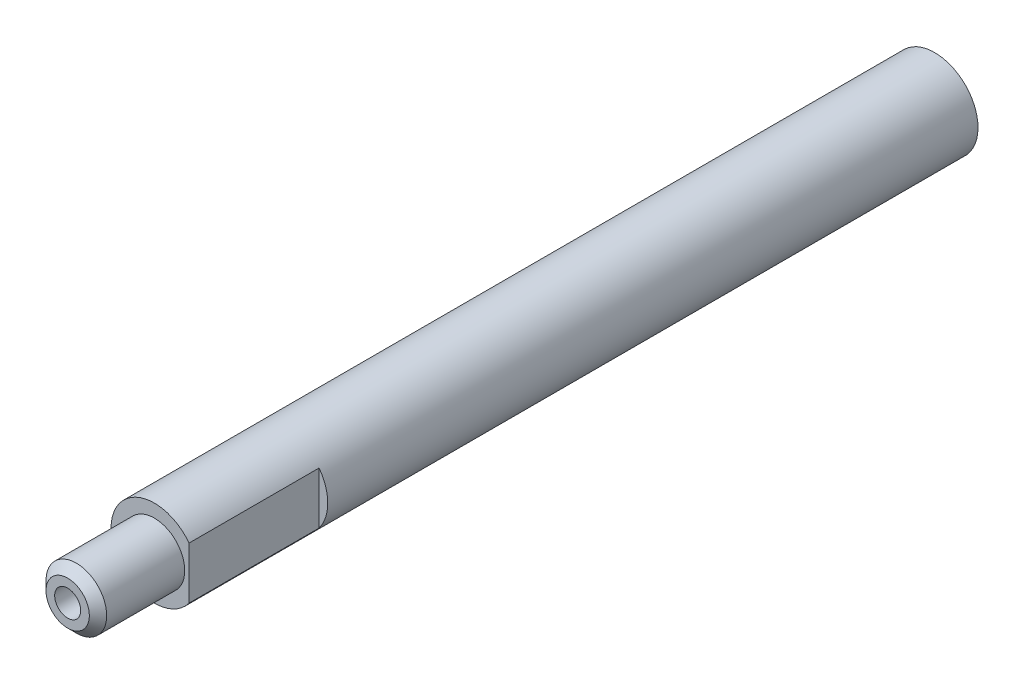
SolidWorks part; units mm, degrees
ref_plane "Front Plane" through (0, 0, 0) normal (0, 0, 1) x (1, 0, 0)
ref_plane "Top Plane" through (0, 0, 0) normal (0, 1, 0) x (1, 0, 0)
ref_plane "Right Plane" through (0, 0, 0) normal (1, 0, 0) x (0, 0, -1)
sketch "Sketch1" plane through (0, 0, 0) normal (0, 0, 1) x (1, 0, 0)
  circle A0 centre (0, 0) radius 5
  dimension "D1" = 10
extrude "Base Extrude" add sketch "Sketch1" along normal blind 100
sketch "Sketch7" plane through (0, 0, 100) normal (0, 0, 1) x (1, 0, 0)
  circle A0 centre (0, 0) radius 3.5
  dimension "D1" = 7
extrude "Front Cut" cut sketch "Sketch7" against normal blind 10 flip side to cut
hole_wizard "Front Hole" positions "Sketch2" profile "Sketch3" hole size "Ø3.0" standard "ANSI Metric"
sketch "Sketch2" plane through (0, 0, 100) normal (0, 0, 1) x (1, 0, 0)
  point P0 (0, 0)
sketch "Sketch3" plane through (0, 0, 100) normal (1, 0, 0) x (0, -1, 0)
  line L0 (0, 0) -> (0, 10.9013)
  line L1 (0, 10.9013) -> (1.5, 10)
  line L2 (1.5, 10) -> (1.5, 0)
  line L5 (1.5, 0) -> (0, 0)
  line L10 (0, 10.9013) -> (-1.5, 10) construction
  line L11 (0, -6.35) -> (0, 107.95) construction
  dimension "Hole Dia." = 3
  dimension "Hole Depth" = 10
  dimension "Drill Angle" = 118
chamfer "Chamfer1" distance 1 angle 45 1 edges at (3.5, 0, 100)
sketch "Keyway" plane through (0, 0, 90) normal (0, 0, 1) x (1, 0, 0)
  line L0 (4, 3) -> (4, -3)
  circle A1 centre (0, 0) radius 2.5
  circle A3 centre (0, 0) radius 5 construction
  circle A4 centre (0, 0) radius 2.5
  arc A5 (4, -3) -> (4, 3) centre (0, 0) ccw
  dimension "D2" = 6
  dimension "D1" = 0
extrude "Keyway Cut" cut sketch "Keyway" against normal blind 15 contours A5 L0
hole_wizard "Ø4.0 (4) Black Hole" positions "Sketch5" profile "Sketch6" hole size "Ø4.0" standard "ANSI Metric"
sketch "Sketch5" plane through (0, 0, 0) normal (0, 0, -1) x (-1, 0, 0)
  point P0 (0, 0)
sketch "Sketch6" plane through (0, 0, 0) normal (1, 0, 0) x (0, 1, 0)
  line L0 (0, 0) -> (0, 21.2017)
  line L1 (0, 21.2017) -> (2, 20)
  line L2 (2, 20) -> (2, 0)
  line L5 (2, 0) -> (0, 0)
  line L10 (0, 21.2017) -> (-2, 20) construction
  line L11 (0, -6.35) -> (0, 107.95) construction
  dimension "Hole Dia." = 4
  dimension "Hole Depth" = 20
  dimension "Drill Angle" = 118
